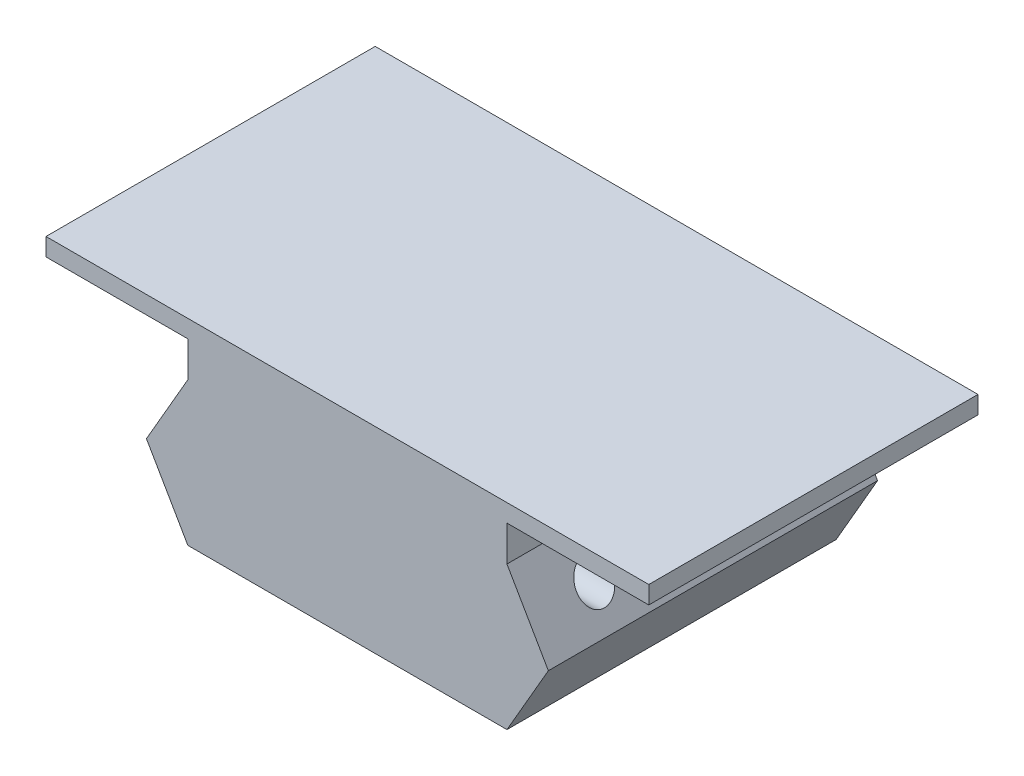
SolidWorks part; units mm, degrees
ref_plane "Front Plane" through (0, 0, 0) normal (0, 0, 1) x (1, 0, 0)
ref_plane "Top Plane" through (0, 0, 0) normal (0, 1, 0) x (1, 0, 0)
ref_plane "Right Plane" through (0, 0, 0) normal (1, 0, 0) x (0, 0, -1)
sketch "Sketch1" plane through (0, 0, 0) normal (0, 0, 1) x (1, 0, 0)
  line L0 (0, 0) -> (9.693, 0) construction
  line L1 (9.693, 0) -> (-8.307, 0)
  line L2 (-8.307, 0) -> (-10.642, 4.0443)
  line L3 (-10.642, 4.0443) -> (-8.307, 8.0887)
  line L5 (9.693, 8.0887) -> (12.028, 4.0443)
  line L6 (12.028, 4.0443) -> (9.693, 0)
  line L7 (-8.307, 8.0887) -> (-8.307, 10.0887)
  line L8 (-8.307, 10.0887) -> (-16.307, 10.0887)
  line L9 (-16.307, 10.0887) -> (-16.307, 11.0887)
  line L10 (-16.307, 11.0887) -> (17.693, 11.0887)
  line L11 (17.693, 11.0887) -> (17.693, 10.0887)
  line L12 (17.693, 10.0887) -> (9.693, 10.0887)
  line L13 (9.693, 10.0887) -> (9.693, 8.0887)
  dimension "D1" = 18
  dimension "D2" = 120
  dimension "D3" = 120
  dimension "D4" = 120
  dimension "D5" = 120
  dimension "D6" = 4.67
  dimension "D7" = 34
  dimension "D8" = 2
  dimension "D9" = 8
extrude "Boss-Extrude1" add sketch "Sketch1" against normal blind 18.5684 contours L10 L11 L12 L13 L5 L6 L1 L2 L3 L7 L8 L9
sketch "Sketch2" plane through (0, 0, 0) normal (1, 0, 0) x (0, 0, -1)
  line L0 (18.5684, 8.0887) -> (0, 8.0887) construction
  line L1 (0, 6.0988) -> (0, -6.0988) construction
  line L2 (18.5684, 8.0887) -> (18.5684, 4.0443) construction
  circle A0 centre (3.71, 5.9887) radius 1
  circle A1 centre (7.42, 5.9887) radius 1
  circle A2 centre (11.13, 5.9887) radius 1
  circle A3 centre (14.84, 5.9887) radius 1
  point P8 (0, 0)
  dimension "D1" = 2
  dimension "D2" = 2.1
  dimension "D3" = 3.71
  dimension "D4" = 18.5684
  dimension "D5" = 3.71
  dimension "D6" = 3.71
  dimension "D7" = 3.71
extrude "Cut-Extrude1" cut sketch "Sketch2" against normal through all both and the other way through all
